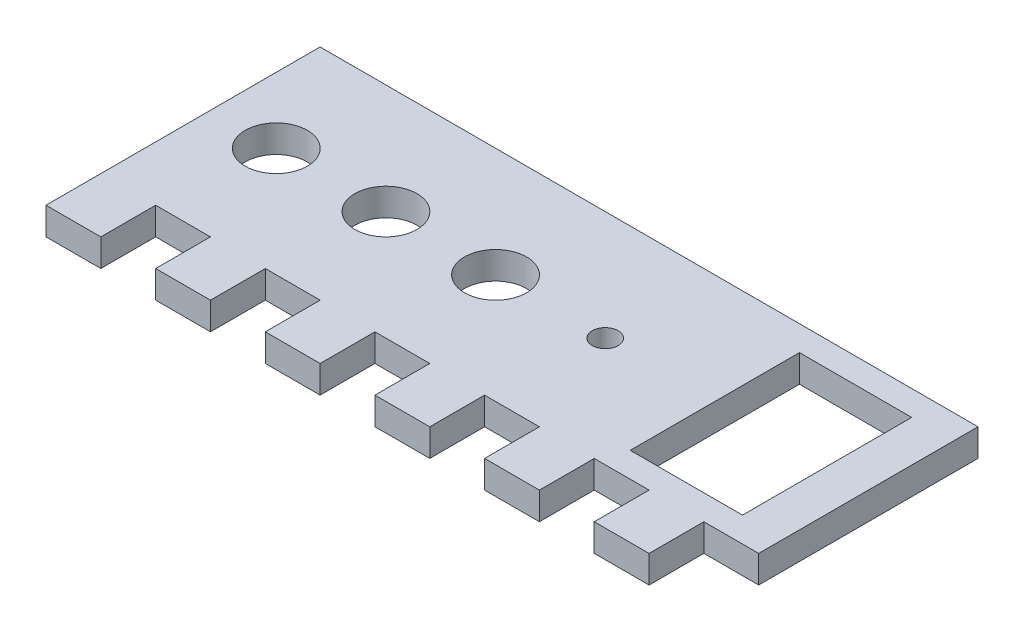
SolidWorks part; units mm, degrees
ref_plane "Front Plane" through (0, 0, 0) normal (0, 0, 1) x (1, 0, 0)
ref_plane "Top Plane" through (0, 0, 0) normal (0, 1, 0) x (1, 0, 0)
ref_plane "Right Plane" through (0, 0, 0) normal (1, 0, 0) x (0, 0, -1)
sketch "Sketch1" plane through (0, 0, 0) normal (0, 1, 0) x (1, 0, 0)
  line L0 (0, 0) -> (0, -6.35)
  line L1 (6.35, 0) -> (12.7, 0)
  line L2 (0, 0) -> (0, 25.4)
  line L3 (0, 25.4) -> (76.2, 25.4)
  line L4 (76.2, 0) -> (76.2, 25.4)
  line L5 (58.42, 22.5) -> (71.42, 22.5)
  line L6 (58.42, 22.5) -> (58.42, 2.9)
  line L7 (58.42, 2.9) -> (71.42, 2.9)
  line L8 (71.42, 22.5) -> (71.42, 2.9)
  line L9 (0, -6.35) -> (6.35, -6.35)
  line L10 (6.35, -6.35) -> (6.35, 0)
  line L11 (12.7, -6.35) -> (19.05, -6.35)
  line L12 (19.05, -6.35) -> (19.05, 0)
  line L13 (12.7, 0) -> (12.7, -6.35)
  line L14 (25.4, -6.35) -> (31.75, -6.35)
  line L15 (31.75, -6.35) -> (31.75, 0)
  line L16 (25.4, 0) -> (25.4, -6.35)
  line L17 (38.1, -6.35) -> (44.45, -6.35)
  line L18 (44.45, -6.35) -> (44.45, 0)
  line L19 (38.1, 0) -> (38.1, -6.35)
  line L20 (50.8, -6.35) -> (57.15, -6.35)
  line L21 (57.15, -6.35) -> (57.15, 0)
  line L22 (50.8, 0) -> (50.8, -6.35)
  line L23 (63.5, -6.35) -> (69.85, -6.35)
  line L24 (69.85, -6.35) -> (69.85, 0)
  line L25 (63.5, 0) -> (63.5, -6.35)
  line L26 (19.05, 0) -> (25.4, 0)
  line L27 (31.75, 0) -> (38.1, 0)
  line L28 (44.45, 0) -> (50.8, 0)
  line L29 (57.15, 0) -> (63.5, 0)
  line L30 (69.85, 0) -> (76.2, 0)
  circle A4 centre (7.62, 12.7) radius 3.6
  circle A5 centre (20.32, 12.7) radius 3.6
  circle A6 centre (33.02, 12.7) radius 3.6
  circle A7 centre (45.72, 12.7) radius 1.5
  point P27 (58.42, 12.7)
  dimension "D4" = 6.35
  dimension "D5" = 6.35
  dimension "D6" = 6
  dimension "D15" = 7.2
  dimension "D16" = 7.2
  dimension "D17" = 7.2
  dimension "D19" = 0
  dimension "D24" = 3
  dimension "D1" = 76.2
  dimension "D2" = 25.4
  dimension "D18" = 0
  dimension "D20" = 12.7
  dimension "D21" = 12.7
  dimension "D22" = 7.62
  dimension "D23" = 12.7
  dimension "D25" = 0
  dimension "D26" = 12.7
  dimension "D27" = 13
  dimension "D28" = 19.6
  dimension "D29" = 0
  dimension "D30" = 12.7
extrude "Boss-Extrude1" add sketch "Sketch1" along normal blind 3.175
